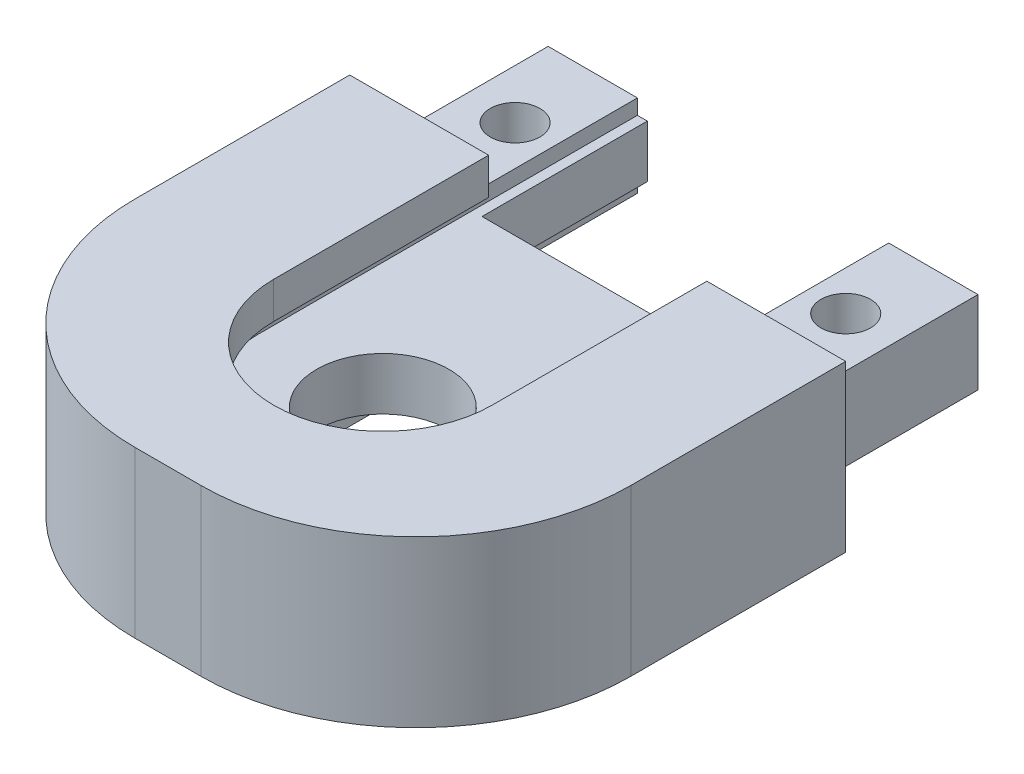
SolidWorks part; units mm, degrees
ref_plane "Front Plane" through (0, 0, 0) normal (0, 0, 1) x (1, 0, 0)
ref_plane "Top Plane" through (0, 0, 0) normal (0, 1, 0) x (1, 0, 0)
ref_plane "Right Plane" through (0, 0, 0) normal (1, 0, 0) x (0, 0, -1)
sketch "Sketch1" plane through (0, 0, 0) normal (0, 1, 0) x (1, 0, 0)
  line L0 (0, 0) -> (6, 0)
  line L1 (6, 0) -> (6, -10)
  line L2 (6, -10) -> (20, -10)
  line L3 (20, -10) -> (20, 0)
  line L4 (20, 0) -> (26, 0)
  line L5 (26, 0) -> (26, -10)
  line L7 (0, -10) -> (0, 0)
  line L8 (0, -10) -> (-2, -10)
  line L11 (28, -36) -> (28, -10)
  line L12 (28, -10) -> (26, -10)
  line L13 (3, 0) -> (3, -5) construction
  line L14 (13, -10) -> (13, 0) construction
  line L15 (28, -36) -> (-2, -36)
  line L16 (-2, -36) -> (-2, -10)
  circle A0 centre (3, -5) radius 1.5
  circle A1 centre (23, -5) radius 1.5
  dimension "D9" = 3
  dimension "D1" = 36
  dimension "D2" = 30
  dimension "D3" = 10
  dimension "D4" = 6
  dimension "D5" = 2
  dimension "D6" = 6
  dimension "D7" = 2
  dimension "D8" = 5
extrude "Boss-Extrude1" add sketch "Sketch1" along normal blind 5
sketch "Sketch2" plane through (0, 0, 36) normal (0, 0, 1) x (1, 0, 0)
  line L0 (-2, 5) -> (-2, 7.5)
  line L1 (-2, 7.5) -> (28, 7.5)
  line L2 (28, 7.5) -> (28, 5)
  line L3 (28, 5) -> (-2, 5)
  line L4 (-2, 0) -> (28, 0)
  line L5 (28, 0) -> (28, -2.5)
  line L6 (28, -2.5) -> (-2, -2.5)
  line L7 (-2, -2.5) -> (-2, 0)
  point P12 (27.9848, 5)
  dimension "D1" = 10
extrude "Boss-Extrude2" add sketch "Sketch2" against normal up to surface (26 mm away) up to face at (13, 2.5, 10)
fillet "Fillet1" radius 13 2 edges at (28, 2.5, 36) (-2, 2.5, 36)
ref_plane "Plane1" through (0, 2.5, 0) normal (0, -1, 0) x (-1, 0, 0)
sketch "Sketch3" plane through (0, 0, 10) normal (0, 0, -1) x (-1, 0, 0)
  line L0 (-19.6, 7.5) -> (-19.6, 5.2875)
  line L1 (2, 7.5) -> (-28, 7.5) construction
  line L2 (-19.6, 5.2875) -> (-20.6, 5.2875)
  line L3 (-20.6, 5.2875) -> (-20.6, 4.0875)
  line L4 (-20.6, 4.0875) -> (-13, 4.0875)
  line L5 (-13, 4.0875) -> (-5.4, 4.0875)
  line L6 (-5.4, 4.0875) -> (-5.4, 5.2875)
  line L7 (-5.4, 5.2875) -> (-6.4, 5.2875)
  line L8 (-6.4, 5.2875) -> (-6.4, 7.5)
  line L9 (-6.4, 7.5) -> (-19.6, 7.5)
  line L10 (-20, 2.5) -> (-6, 2.5) construction
  line L11 (-20, 5) -> (-20, 0) construction
  line L12 (-6, 5) -> (-6, 0) construction
  line L13 (-13, 2.5) -> (-13, 4.0875) construction
  point P18 (-10.7323, 2.1125)
  point P19 (-19.8114, 2.1125)
  dimension "D1" = 1.2
  dimension "D2" = 3.4125
  dimension "D3" = 13.2
  dimension "D4" = 15.2
extrude "Cut-Extrude1" cut sketch "Sketch3" against normal blind 13 and the other way through all
sketch "Sketch4" plane through (0, 4.0875, 0) normal (0, 1, 0) x (1, 0, 0)
  line L0 (6.4, -23) -> (19.6, -23) construction
  circle A0 centre (13, -23) radius 7.6
  dimension "D1" = 15.2
extrude "Cut-Extrude2" cut sketch "Sketch4" along normal up to surface (1.2 mm away) up to face at (5.9, 5.2875, 16.5)
sketch "Sketch5" plane through (0, 4.0875, 0) normal (0, 1, 0) x (1, 0, 0)
  line L0 (6.4, -23) -> (19.6, -23) construction
  circle A0 centre (13, -23) radius 6.6
  dimension "D1" = 13.2
extrude "Cut-Extrude3" cut sketch "Sketch5" along normal through all
mirror "Mirror1" about plane through (0, 2.5, 0) normal (0, -1, 0) of "Cut-Extrude1"
sketch "Sketch6" plane through (0, 0.9125, 0) normal (0, -1, 0) x (1, 0, 0)
  line L0 (6.4, 23) -> (19.6, 23) construction
  circle A0 centre (13, 23) radius 7.6
  dimension "D1" = 15.2
extrude "Cut-Extrude4" cut sketch "Sketch6" along normal up to surface (1.2 mm away) up to face at (5.9, -0.2875, 16.5)
sketch "Sketch7" plane through (0, 0.9125, 0) normal (0, -1, 0) x (1, 0, 0)
  line L0 (6.4, 23) -> (19.6, 23) construction
  circle A0 centre (13, 23) radius 6.6
  dimension "D1" = 13.2
extrude "Cut-Extrude5" cut sketch "Sketch7" along normal through all
sketch "Sketch8" plane through (0, 4.0875, 0) normal (0, 1, 0) x (1, 0, 0)
  circle A0 centre (13, -23) radius 4
  dimension "D1" = 8
extrude "Cut-Extrude6" cut sketch "Sketch8" against normal through all
